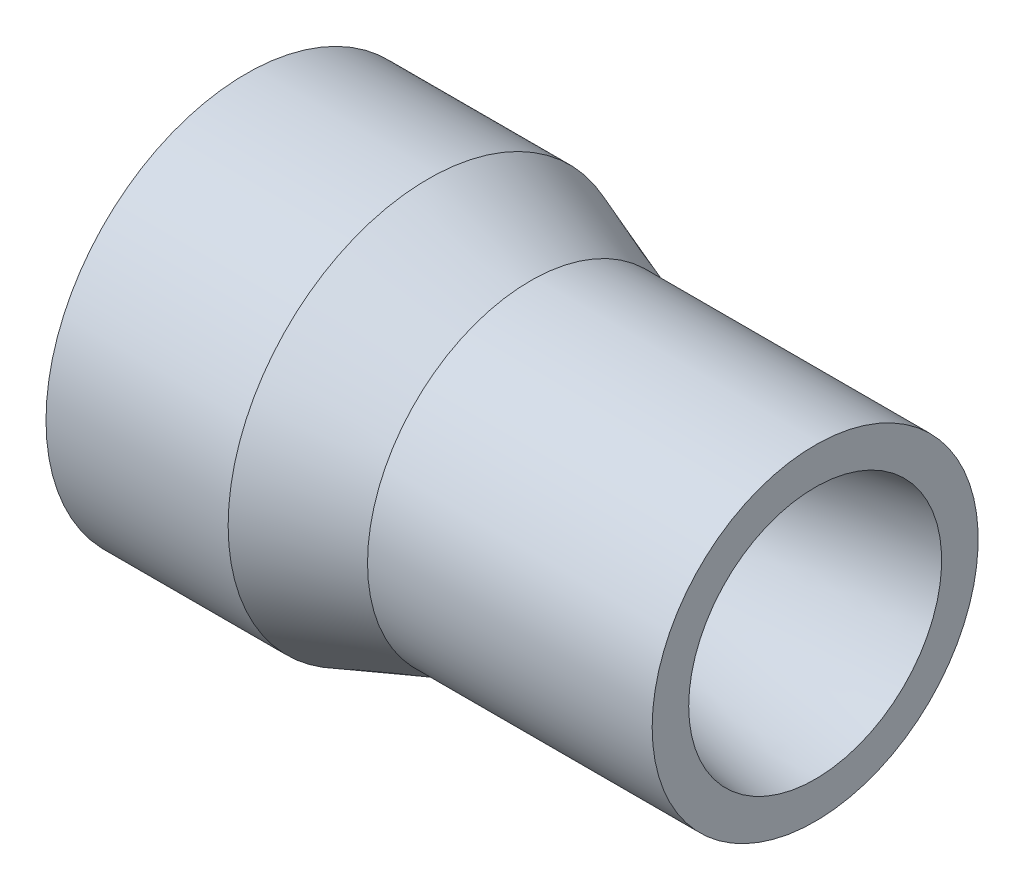
SolidWorks part; units mm, degrees
material "Ex-70 Graphite"
ref_plane "Front Plane" through (0, 0, 0) normal (0, 0, 1) x (1, 0, 0)
ref_plane "Top Plane" through (0, 0, 0) normal (0, 1, 0) x (1, 0, 0)
ref_plane "Right Plane" through (0, 0, 0) normal (1, 0, 0) x (0, 0, -1)
sketch "Sketch1" plane through (0, 0, 0) normal (0, 0, 1) x (1, 0, 0)
  line L0 (0, 0) -> (176.8872, 0) construction
  line L1 (0, 42.8625) -> (27.5254, 42.8625) construction
  line L2 (54.4274, 15.285) -> (96.5346, 15.285) construction
  line L3 (40.0098, 31.4386) -> (62.67, 18.3557)
  line L7 (0, 42.8625) -> (0, 52.197)
  line L11 (76.0448, 15.6078) -> (93.9614, 21.826) construction
  line L13 (148.34, 32.975) -> (123.0603, 29.4222) construction
  line L14 (148.34, 32.975) -> (148.34, 42.5)
  line L15 (148.34, 42.5) -> (74.13, 42.5)
  line L17 (74.13, 42.5) -> (47.4877, 52.197)
  line L18 (47.4877, 52.197) -> (0, 52.197)
  arc A0 (0, 42.8625) -> (40.0098, 31.4386) centre (-2.7952, -42.7019) cw
  arc A1 (74.13, 15.285) -> (62.67, 18.3557) centre (74.13, 38.205) cw
  arc A2 (74.13, 15.285) -> (76.0448, 15.6078) centre (74.13, 21.125) ccw
  spline S0 degree 3 poles (76.0448, 15.6078) (97.2352, 22.9623) (126.0123, 29.837) (148.34, 32.975) knots 0 0 0 0 1 1 1 1
  dimension "D4" = 22.92
  dimension "D5" = 74.13
  dimension "D7" = 5.84
  dimension "D11" = 52.197
  dimension "D6" = 30
  dimension "D3" = 85.61
  dimension "D9" = 74.21
  dimension "D1" = 42.8625
  dimension "D2" = 15.285
  dimension "D8" = 19.14
  dimension "D10" = 32.975
  dimension "D12" = 8
  dimension "D13" = 9.525
  dimension "D14" = 20
revolve "Revolve1" add sketch "Sketch1" angle 360 about L0
